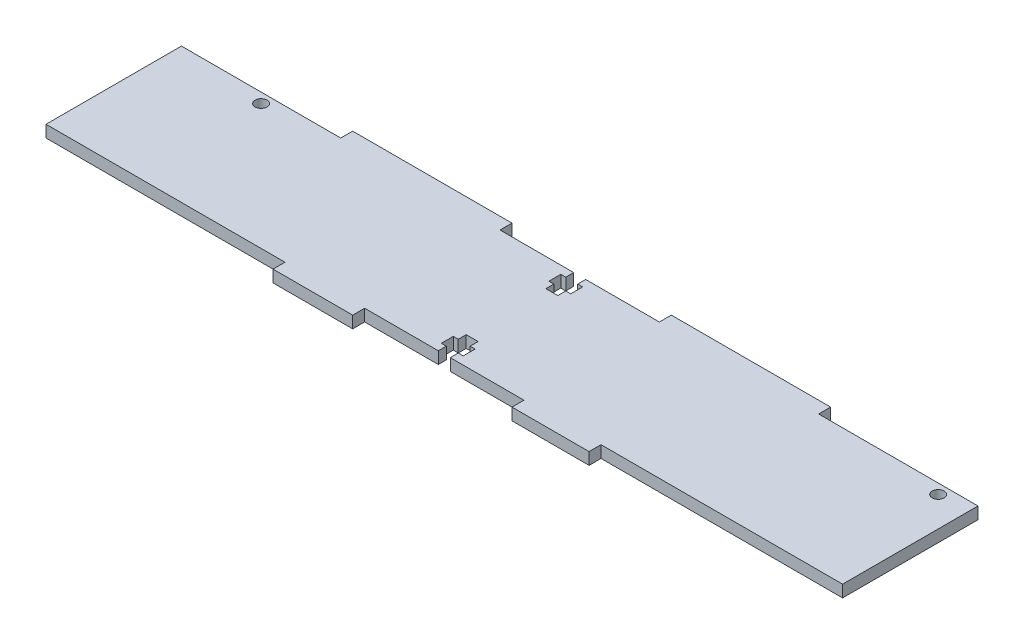
SolidWorks part; units mm, degrees
ref_plane "Front Plane" through (0, 0, 0) normal (0, 0, 1) x (1, 0, 0)
ref_plane "Top Plane" through (0, 0, 0) normal (0, 1, 0) x (1, 0, 0)
ref_plane "Right Plane" through (0, 0, 0) normal (1, 0, 0) x (0, 0, -1)
sketch "Sketch1" plane through (0, 0, 0) normal (0, 1, 0) x (1, 0, 0)
  line L0 (0, 20) -> (0, -20) construction
  line L1 (-100, -20) -> (100, -20)
  line L2 (-100, -20) -> (-100, 20)
  line L3 (-100, 20) -> (100, 20)
  line L4 (100, -20) -> (100, 20)
  line L5 (-100, -20) -> (100, 20) construction
  line L6 (-100, 20) -> (100, -20) construction
  line L7 (-100, 0) -> (100, 0) construction
  point P0 (0, 0)
  dimension "D1" = 40
  dimension "D2" = 200
extrude "Boss-Extrude1" add sketch "Sketch1" along normal blind 3
sketch "Sketch3" plane through (0, 3, 0) normal (0, 1, 0) x (1, 0, 0)
  line L0 (0, -20) -> (0, 20) construction
  line L1 (100, 20) -> (-100, 20) construction
  line L2 (-100, -20) -> (100, -20) construction
  line L3 (-100, 0) -> (100, 0) construction
  line L4 (-100, 20) -> (-100, -20) construction
  line L5 (100, -20) -> (100, 20) construction
  line L14 (-20, -20) -> (-20, -17)
  line L15 (-20, -17) -> (-1.5, -17)
  line L16 (-1.5, -17) -> (-1.5, -15)
  line L17 (-1.5, -15) -> (-2.75, -15)
  line L18 (-2.75, -15) -> (-2.75, -12)
  line L19 (-2.75, -12) -> (-1.5, -12)
  line L20 (-1.5, -12) -> (-1.5, -10)
  line L21 (-1.5, -10) -> (1.5, -10)
  line L22 (-20, -20) -> (20, -20)
  line L23 (1.5, -12) -> (1.5, -10)
  line L24 (2.75, -12) -> (1.5, -12)
  line L25 (2.75, -15) -> (2.75, -12)
  line L26 (1.5, -15) -> (2.75, -15)
  line L27 (1.5, -17) -> (1.5, -15)
  line L28 (20, -17) -> (1.5, -17)
  line L29 (20, -20) -> (20, -17)
  line L30 (-40, -20) -> (-40, -17)
  line L31 (-40, -17) -> (-100, -17)
  line L32 (-100, -17) -> (-100, -20)
  line L33 (-100, -20) -> (-40, -20)
  line L34 (100, -17) -> (100, -20)
  line L35 (39.3506, -17) -> (100, -17)
  line L36 (39.3506, -20) -> (39.3506, -17)
  line L37 (100, -20) -> (39.3506, -20)
  line L85 (85, 17) -> (100, 17)
  line L86 (100, 17) -> (100, 20)
  line L87 (100, 20) -> (60, 20)
  line L88 (60, 20) -> (60, 17)
  line L89 (60, 17) -> (82, 17)
  line L101 (20, 20) -> (20, 17)
  line L102 (20, 17) -> (1.5, 17)
  line L103 (1.5, 17) -> (1.5, 15)
  line L104 (1.5, 15) -> (2.75, 15)
  line L105 (2.75, 15) -> (2.75, 12)
  line L106 (2.75, 12) -> (1.5, 12)
  line L107 (1.5, 12) -> (1.5, 10)
  line L108 (-20, 20) -> (20, 20)
  line L109 (-1.5, 10) -> (1.5, 10)
  line L110 (-1.5, 12) -> (-1.5, 10)
  line L111 (-2.75, 12) -> (-1.5, 12)
  line L112 (-2.75, 15) -> (-2.75, 12)
  line L113 (-1.5, 15) -> (-2.75, 15)
  line L114 (-1.5, 17) -> (-1.5, 15)
  line L115 (-20, 17) -> (-1.5, 17)
  line L116 (-20, 20) -> (-20, 17)
  line L117 (82, 17) -> (85, 17)
  line L118 (-60, 20) -> (-60, 17)
  line L119 (-100, 20) -> (-60, 20)
  line L120 (-100, 17) -> (-100, 20)
  line L121 (-85, 17) -> (-100, 17)
  line L122 (-82, 17) -> (-85, 17)
  line L123 (-60, 17) -> (-82, 17)
  point P17 (0, -17)
  point P23 (0, -10)
  point P90 (0, 10)
  point P91 (0, 17)
  dimension "D2" = 3
  dimension "D3" = 3
  dimension "D4" = 3
  dimension "D9" = 3
  dimension "D10" = 5.5
  dimension "D12" = 3
extrude "Cut-Extrude1" cut sketch "Sketch3" against normal blind 3
sketch "Sketch4" plane through (0, 3, 0) normal (0, 1, 0) x (1, 0, 0)
  circle A0 centre (92.5, 14.5) radius 1.5
  circle A1 centre (-77.5, 14.5) radius 1.5
extrude "Cut-Extrude2" cut sketch "Sketch4" against normal blind 3
